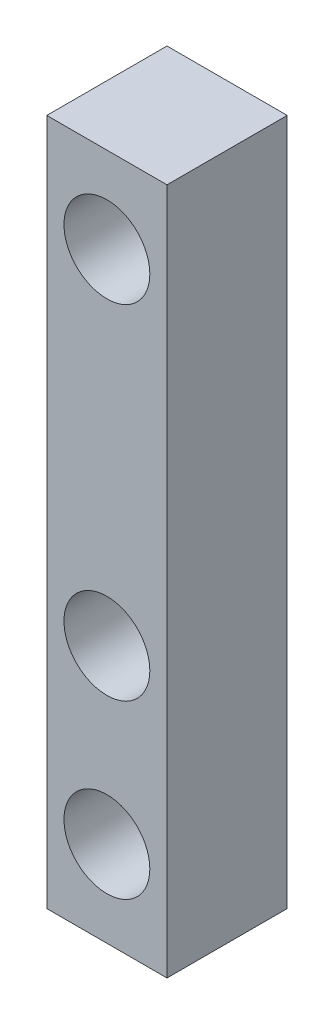
SolidWorks part; units mm, degrees
ref_plane "Front Plane" through (0, 0, 0) normal (0, 0, 1) x (1, 0, 0)
ref_plane "Top Plane" through (0, 0, 0) normal (0, 1, 0) x (1, 0, 0)
ref_plane "Right Plane" through (0, 0, 0) normal (1, 0, 0) x (0, 0, -1)
sketch "Sketch1" plane through (0, 0, 0) normal (0, 0, 1) x (1, 0, 0)
  line L1 (0, 0) -> (7, 0)
  line L2 (0, 0) -> (0, 40)
  line L3 (0, 40) -> (7, 40)
  line L4 (7, 0) -> (7, 40)
  dimension "D1" = 40
  dimension "D2" = 7
extrude "Boss-Extrude1" add sketch "Sketch1" along normal blind 7
sketch "Sketch2" plane through (0, 0, 7) normal (0, 0, 1) x (1, 0, 0)
  line L0 (0, 40) -> (0, 0) construction
  line L1 (7, 40) -> (0, 40) construction
  line L2 (0, 0) -> (7, 0) construction
  circle A0 centre (3.5, 5) radius 2.5
  circle A1 centre (3.5, 15) radius 2.5
  circle A2 centre (3.5, 35) radius 2.5
  dimension "D4" = 5
  dimension "D5" = 5
  dimension "D6" = 5
  dimension "D1" = 3.5
  dimension "D2" = 3.5
  dimension "D3" = 3.5
  dimension "D7" = 5
  dimension "D8" = 5
  dimension "D9" = 10
extrude "Cut-Extrude1" cut sketch "Sketch2" against normal blind 7
equation "\"link_length\"= 40"
equation "\"D1@Sketch1\"=\"link_length\""
equation "\"link_width\"=7"
equation "\"D2@Sketch1\"=\"link_width\""
equation "\"link_thickness\"=7"
equation "\"D1@Boss-Extrude1\"=\"link_thickness\""
equation "\"D1@Sketch2\"= \"link_width\"/2"
equation "\"D2@Sketch2\"= \"link_width\"/2"
equation "\"D3@Sketch2\"= \"link_width\"/2"
equation "\"pin_d\"=5"
equation "\"D4@Sketch2\"=\"pin_d\""
equation "\"D5@Sketch2\"=\"pin_d\""
equation "\"D7@Sketch2\"= \"pin_d\""
equation "\"D8@Sketch2\"= \"pin_d\""
equation "\"D9@Sketch2\"= \"pin_d\"*2"
equation "\"D1@Cut-Extrude1\"= \"link_thickness\""
